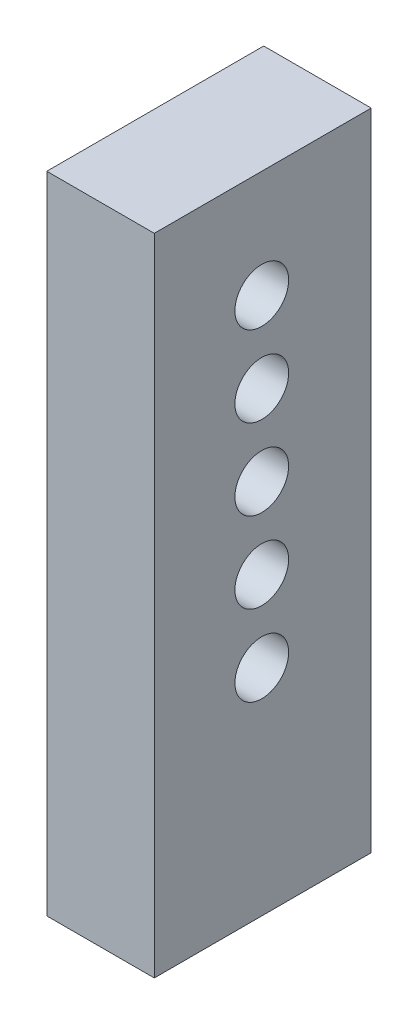
SolidWorks part; units mm, degrees
ref_plane "Front Plane" through (0, 0, 0) normal (0, 0, 1) x (1, 0, 0)
ref_plane "Top Plane" through (0, 0, 0) normal (0, 1, 0) x (1, 0, 0)
ref_plane "Right Plane" through (0, 0, 0) normal (1, 0, 0) x (0, 0, -1)
sketch "Sketch1" plane through (0, 0, 0) normal (1, 0, 0) x (0, 0, -1)
  line L0 (-101.6, 0) -> (-50.3396, 0)
  line L1 (-50.3396, 0) -> (-50.3396, 152.4)
  line L6 (-101.6, 152.4) -> (-101.6, 0)
  line L9 (-101.6, 152.4) -> (-50.3396, 152.4)
  circle A0 centre (-76.2, 50.8) radius 6.35
  circle A1 centre (-76.2, 69.85) radius 6.35
  circle A2 centre (-76.2, 88.9) radius 6.35
  circle A3 centre (-76.2, 107.95) radius 6.35
  circle A4 centre (-76.2, 127) radius 6.35
  dimension "D4" = 19.05
  dimension "D5" = 19.05
  dimension "D6" = 19.05
  dimension "D7" = 19.05
  dimension "D8" = 152.4
extrude "Boss-Extrude1" add sketch "Sketch1" along normal blind 25.4
sketch "Sketch6" plane through (0, 0, 0) normal (0, -1, 0) x (1, 0, 0)
  line L0 (0, 101.6) -> (0, 50.3396) construction
  line L1 (25.4, 50.3396) -> (0, 50.3396) construction
  circle A0 centre (12.7, 75.7396) radius 2.0193
  dimension "D3" = 4.0386
  dimension "D1" = 12.7
  dimension "D2" = 25.4
extrude "Cut-Extrude4" cut sketch "Sketch6" against normal blind 25.4
